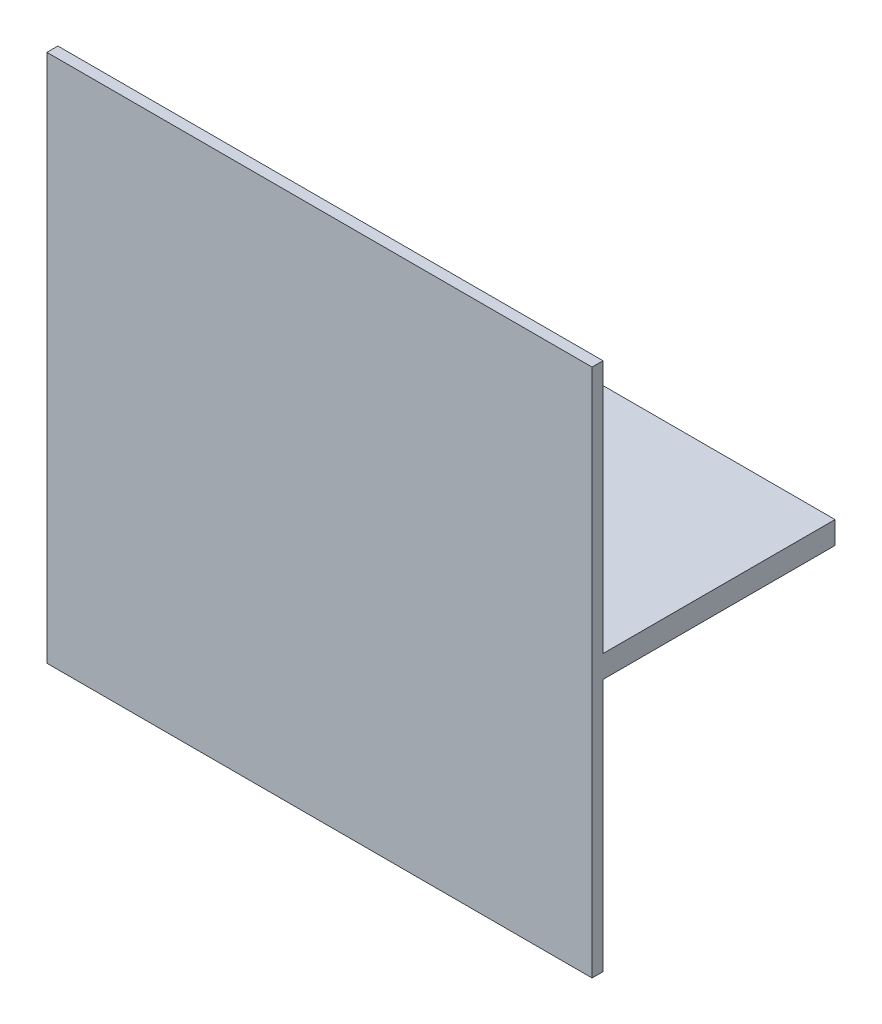
SolidWorks part; units mm, degrees
ref_plane "Front Plane" through (0, 0, 0) normal (0, 0, 1) x (1, 0, 0)
ref_plane "Top Plane" through (0, 0, 0) normal (0, 1, 0) x (1, 0, 0)
ref_plane "Right Plane" through (0, 0, 0) normal (1, 0, 0) x (0, 0, -1)
sketch "Sketch2" plane through (0, 0, 0) normal (0, 1, 0) x (1, 0, 0)
  line L1 (-1101.6089, 160.7467) -> (-852.9889, 160.7467)
  line L2 (-1101.6089, 160.7467) -> (-1101.6089, 165.7467)
  line L3 (-1101.6089, 165.7467) -> (-852.9889, 165.7467)
  line L4 (-852.9889, 160.7467) -> (-852.9889, 165.7467)
  dimension "D1" = 248.62
  dimension "D2" = 5
extrude "Boss-Extrude1" add sketch "Sketch2" along normal blind 241.3
sketch "Sketch3" plane through (0, 0, -165.7467) normal (0, 0, -1) x (-1, 0, 0)
  line L0 (1101.6089, 120.65) -> (852.9889, 120.65) construction
  line L1 (1101.6089, 241.3) -> (1101.6089, 0) construction
  line L2 (852.9889, 241.3) -> (852.9889, 0) construction
  line L3 (1101.6089, 120.65) -> (1101.6089, 122.15) construction
  line L4 (852.9889, 120.65) -> (852.9889, 118.9123) construction
  line L5 (1101.6089, 122.15) -> (1101.6089, 125.65) construction
  line L6 (852.9889, 118.9123) -> (852.9889, 115.4123) construction
  line L7 (852.9889, 120.65) -> (853.9889, 120.65) construction
  line L8 (1101.6089, 125.65) -> (852.9889, 125.65)
  line L9 (1101.6089, 125.65) -> (1101.6089, 115.4123)
  line L10 (1101.6089, 115.4123) -> (852.9889, 115.4123)
  line L11 (852.9889, 125.65) -> (852.9889, 115.4123)
  line L12 (852.9889, 120.65) -> (857.9889, 120.65) construction
  line L13 (1101.6089, 120.65) -> (1096.6089, 120.65) construction
  line L14 (857.9889, 120.65) -> (862.9889, 120.65) construction
  line L19 (1101.6089, 120.65) -> (1091.6089, 120.65) construction
  line L21 (1091.6089, 122.15) -> (862.9889, 122.15)
  line L22 (1091.6089, 122.15) -> (1091.6089, 118.9123)
  line L23 (1091.6089, 118.9123) -> (862.9889, 118.9123)
  line L24 (862.9889, 122.15) -> (862.9889, 118.9123)
extrude "Boss-Extrude2" add sketch "Sketch3" along normal blind 105.84
